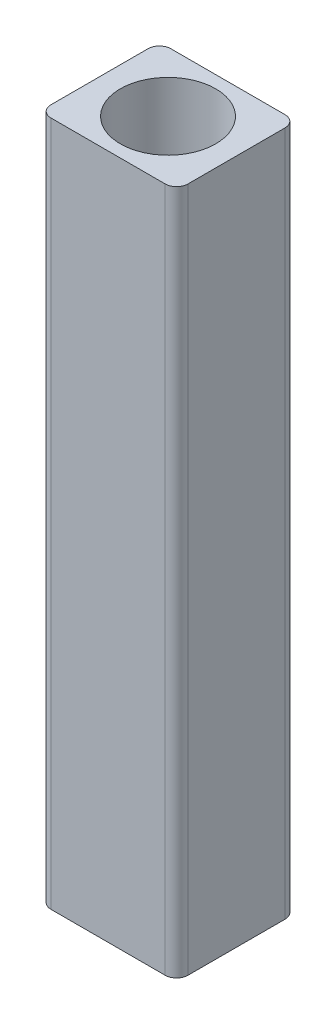
SolidWorks part; units mm, degrees
ref_plane "Front Plane" through (0, 0, 0) normal (0, 0, 1) x (1, 0, 0)
ref_plane "Top Plane" through (0, 0, 0) normal (0, 1, 0) x (1, 0, 0)
ref_plane "Right Plane" through (0, 0, 0) normal (1, 0, 0) x (0, 0, -1)
sketch "Sketch1" plane through (0, 0, 0) normal (0, 1, 0) x (1, 0, 0)
  line L1 (-3.048, -2.667) -> (3.048, -2.667)
  line L2 (-3.048, -2.667) -> (-3.048, 2.667)
  line L3 (-3.048, 2.667) -> (3.048, 2.667)
  line L4 (3.048, -2.667) -> (3.048, 2.667)
  line L5 (-3.048, -2.667) -> (3.048, 2.667) construction
  line L6 (-3.048, 2.667) -> (3.048, -2.667) construction
  circle A0 centre (0, 0) radius 2.122
  dimension "D1" = 4.244
  dimension "D2" = 3.048
extrude "Boss-Extrude1" add sketch "Sketch1" along normal blind 30.48
fillet "Fillet1" radius 0.508 4 edges at (-3.048, 15.24, -2.667) (3.048, 15.24, -2.667) (-3.048, 15.24, 2.667) (3.048, 15.24, 2.667)
